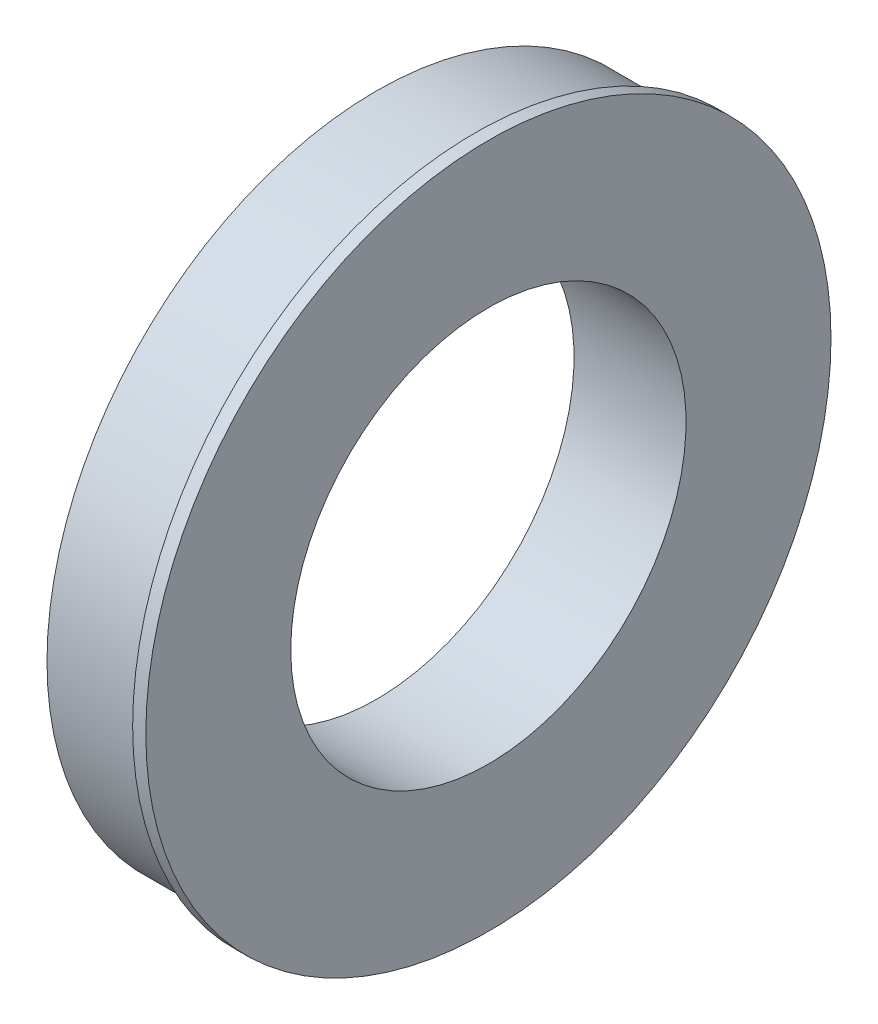
SolidWorks part; units mm, degrees
ref_plane "Front Plane" through (0, 0, 0) normal (0, 0, 1) x (1, 0, 0)
ref_plane "Top Plane" through (0, 0, 0) normal (0, 1, 0) x (1, 0, 0)
ref_plane "Right Plane" through (0, 0, 0) normal (1, 0, 0) x (0, 0, -1)
sketch "Sketch1" plane through (0, 0, 0) normal (1, 0, 0) x (0, 0, -1)
  circle A0 centre (0, 0) radius 63.5
  circle A1 centre (0, 0) radius 38.1
  dimension "D1" = 127
  dimension "D2" = 76.2
extrude "Boss-Extrude3" add sketch "Sketch1" along normal blind 19.05
sketch "Sketch5" plane through (19.05, 0, 0) normal (1, 0, 0) x (0, 0, -1)
  circle A0 centre (0, 0) radius 38.1 construction
  circle A1 centre (0, 0) radius 38.1
  circle A2 centre (0, 0) radius 66.04
  dimension "D1" = 132.08
extrude "Boss-Extrude4" add sketch "Sketch5" along normal blind 2.54
